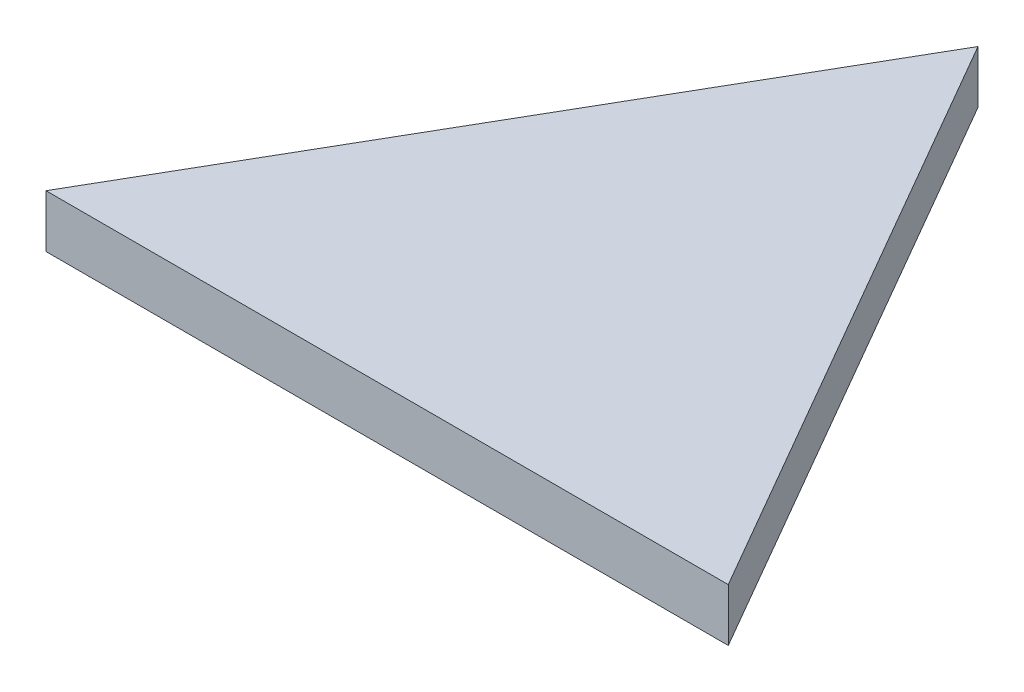
SolidWorks part; units mm, degrees
ref_plane "Front Plane" through (0, 0, 0) normal (0, 0, 1) x (1, 0, 0)
ref_plane "Top Plane" through (0, 0, 0) normal (0, 1, 0) x (1, 0, 0)
ref_plane "Right Plane" through (0, 0, 0) normal (1, 0, 0) x (0, 0, -1)
sketch "Sketch2" plane through (0, 0, 0) normal (0, 1, 0) x (1, 0, 0)
  line L0 (-41.5833, 150.6748) -> (-151.5833, -39.8508)
  line L1 (-151.5833, -39.8508) -> (68.4167, -39.8508)
  line L2 (68.4167, -39.8508) -> (-41.5833, 150.6748)
  dimension "D1" = 220
extrude "Boss-Extrude1" add sketch "Sketch2" along normal blind 17
sketch "Sketch3" plane through (0, 0, 0) normal (0, -1, 0) x (1, 0, 0)
  line L0 (68.4167, 39.8508) -> (-96.5833, -55.412) construction
  line L1 (-41.5833, -150.6748) -> (-151.5833, 39.8508) construction
  line L2 (-151.5833, 39.8508) -> (13.4167, -55.412) construction
  line L3 (68.4167, 39.8508) -> (-41.5833, -150.6748) construction
  line L4 (-41.5833, -150.6748) -> (-41.5833, 39.8508) construction
  line L5 (-151.5833, 39.8508) -> (68.4167, 39.8508) construction
  line L6 (-151.5833, 39.8508) -> (-145.5211, 36.3508) construction
  line L7 (68.4167, 39.8508) -> (62.3545, 36.3508) construction
  circle A1 centre (-145.5211, 36.3508) radius 2
  circle A2 centre (62.3545, 36.3508) radius 2
  circle A3 centre (-41.5833, -143.6748) radius 2
  dimension "D1" = 7
  dimension "D2" = 7
  dimension "D3" = 7
  dimension "D4" = 4
  dimension "D5" = 4
  dimension "D6" = 4
extrude "Cut-Extrude2" cut sketch "Sketch3" against normal blind 14
